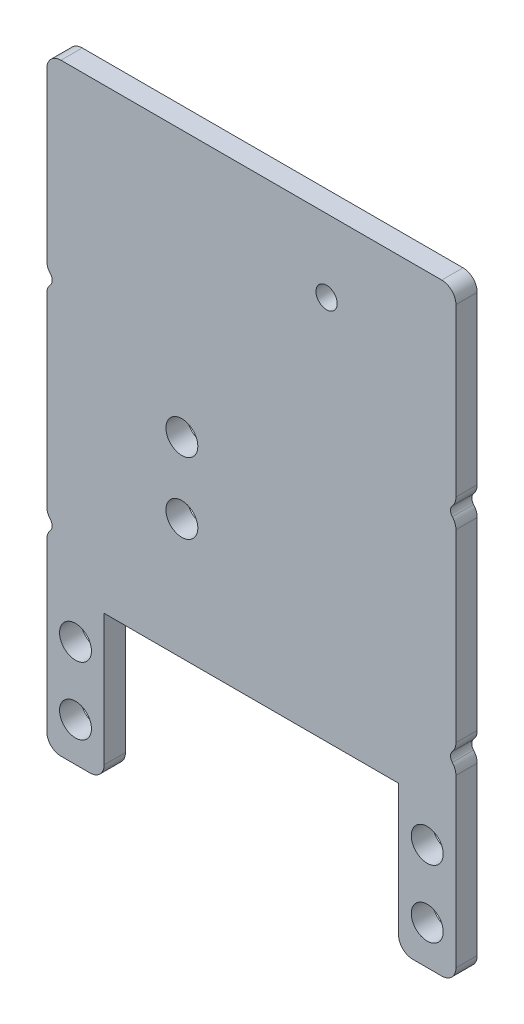
SolidWorks part; units mm, degrees
ref_plane "Front Plane" through (0, 0, 0) normal (0, 0, 1) x (1, 0, 0)
ref_plane "Top Plane" through (0, 0, 0) normal (0, 1, 0) x (1, 0, 0)
ref_plane "Right Plane" through (0, 0, 0) normal (1, 0, 0) x (0, 0, -1)
sketch "Sketch1" plane through (0, 0, 0) normal (0, 0, 1) x (1, 0, 0)
  line L0 (-43.5, -20.5) -> (-47.6, -20.5)
  line L1 (0, 0) -> (-41.5, 0)
  line L2 (0, 0) -> (0, -18.5)
  line L3 (-49.6, -18.5) -> (-49.6, 5)
  line L4 (-41.5, 0) -> (-41.5, -18.5)
  line L5 (-47.6, 64.5) -> (6.1, 64.5)
  line L6 (8.1, 5) -> (8.1, -18.5)
  line L7 (6.1, -20.5) -> (2, -20.5)
  line L8 (-45.55, -1009.5718) -> (-45.55, 48990.4282) construction
  line L9 (4.05, -1007.7666) -> (4.05, 48992.2334) construction
  line L10 (-47.6, 7) -> (6.1, 7) construction
  line L11 (-47.6, 37) -> (6.1, 37) construction
  line L12 (-49.6, 62.5) -> (-49.6, 39)
  line L13 (8.1, 62.5) -> (8.1, 39)
  line L14 (-49.6, 35) -> (-49.6, 9)
  line L15 (8.1, 35) -> (8.1, 9)
  line L16 (-30.55, -980.8388) -> (-30.55, 49019.1612) construction
  line L17 (-10.14, -949.8936) -> (-10.14, 49050.1064) construction
  line L18 (-1036.6947, 54.25) -> (48963.3053, 54.25) construction
  circle A0 centre (-45.55, -5.5) radius 2.25
  circle A1 centre (-45.55, -15) radius 2.25
  circle A2 centre (4.05, -5.5) radius 2.25
  circle A3 centre (4.05, -15) radius 2.25
  arc A4 (7.5907, 36.3333) -> (8.1, 35) centre (6.1, 35) cw
  arc A5 (-49.0907, 36.3333) -> (-49.6, 35) centre (-47.6, 35) ccw
  arc A6 (8.1, 39) -> (7.5907, 37.6667) centre (6.1, 39) cw
  arc A7 (-49.0907, 37.6667) -> (-49.6, 39) centre (-47.6, 39) cw
  arc A8 (8.1, 5) -> (7.5907, 6.3333) centre (6.1, 5) ccw
  arc A9 (-49.0907, 6.3333) -> (-49.6, 5) centre (-47.6, 5) ccw
  arc A10 (8.1, 9) -> (7.5907, 7.6667) centre (6.1, 9) cw
  arc A11 (-49.0907, 7.6667) -> (-49.6, 9) centre (-47.6, 9) cw
  arc A12 (-41.5, -18.5) -> (-43.5, -20.5) centre (-43.5, -18.5) cw
  arc A13 (-47.6, -20.5) -> (-49.6, -18.5) centre (-47.6, -18.5) cw
  arc A14 (0, -18.5) -> (2, -20.5) centre (2, -18.5) ccw
  arc A15 (8.1, -18.5) -> (6.1, -20.5) centre (6.1, -18.5) cw
  arc A16 (8.1, 62.5) -> (6.1, 64.5) centre (6.1, 62.5) ccw
  arc A17 (-47.6, 64.5) -> (-49.6, 62.5) centre (-47.6, 62.5) ccw
  circle A18 centre (-30.55, 17) radius 2.25
  circle A19 centre (-30.55, 27) radius 2.25
  circle A20 centre (-10.14, 54.25) radius 1.5
  arc A21 (7.5907, 7.6667) -> (7.5907, 6.3333) centre (8.3361, 7) ccw
  arc A22 (-49.0907, 7.6667) -> (-49.0907, 6.3333) centre (-49.8361, 7) cw
  arc A23 (7.5907, 37.6667) -> (7.5907, 36.3333) centre (8.3361, 37) ccw
  arc A24 (-49.0907, 36.3333) -> (-49.0907, 37.6667) centre (-49.8361, 37) ccw
  point P24 (-49.6, 7)
  point P26 (8.1, 7)
  point P27 (-49.6, 37)
  point P28 (8.1, 37)
  point P51 (-41.5, -20.5)
  dimension "D8" = 4.5
  dimension "D9" = 4.5
  dimension "D10" = 4.5
  dimension "D11" = 4.5
  dimension "D19" = 2
  dimension "D20" = 2
  dimension "D21" = 2
  dimension "D22" = 2
  dimension "D23" = 2
  dimension "D25" = 4.5
  dimension "D26" = 4.5
  dimension "D31" = 3
  dimension "D32" = 1
  dimension "D1" = 41.5
  dimension "D2" = 20.5
  dimension "D3" = 4.05
  dimension "D4" = 4.05
  dimension "D5" = 4.05
  dimension "D6" = 4.05
  dimension "D7" = 20.5
  dimension "D12" = 9.5
  dimension "D13" = 9.5
  dimension "D14" = 5.5
  dimension "D15" = 5.5
  dimension "D16" = 7
  dimension "D17" = 30
  dimension "D18" = 27.5
  dimension "D24" = 38.65
  dimension "D27" = 10
  dimension "D28" = 10
  dimension "D29" = 10.14
  dimension "D30" = 10.25
extrude "Boss-Extrude1" add sketch "Sketch1" along normal blind 3 contours L5 A17 L12 A7 A5 L14 A11 A9 L3 A13 L0 A12 L4 L1 L2 A14 L7 A15 L6 A8 A10 L15 A4 A6 L13 A16 A0 A1 A2 A3
